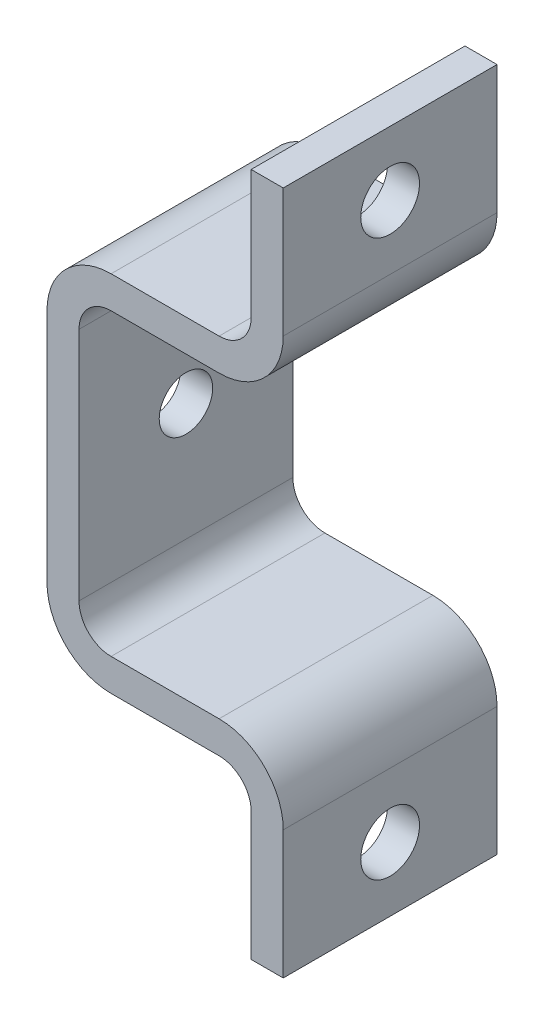
SolidWorks part; units mm, degrees
ref_plane "Front Plane" through (0, 0, 0) normal (0, 0, 1) x (1, 0, 0)
ref_plane "Top Plane" through (0, 0, 0) normal (0, 1, 0) x (1, 0, 0)
ref_plane "Right Plane" through (0, 0, 0) normal (1, 0, 0) x (0, 0, -1)
sketch "Sketch1" plane through (0, 0, 0) normal (0, 0, 1) x (1, 0, 0)
  line L0 (0, -17) -> (0, 17)
  line L1 (0, 17) -> (19.1, 17)
  line L2 (19.1, 17) -> (19.1, 32)
  line L3 (19.1, 32) -> (22.1, 32)
  line L4 (22.1, 32) -> (22.1, 14)
  line L5 (22.1, 14) -> (3, 14)
  line L6 (3, 14) -> (3, -14)
  line L7 (0, 0) -> (30452.2574, 0) construction
  line L8 (22.1, -32) -> (22.1, -14)
  line L9 (19.1, -32) -> (22.1, -32)
  line L10 (19.1, -17) -> (19.1, -32)
  line L11 (0, -17) -> (19.1, -17)
  line L12 (22.1, -14) -> (3, -14)
  point P4 (0, 0)
  point P11 (0, 0)
  point P20 (3, 0)
  dimension "D1" = 3
  dimension "D2" = 3
  dimension "D3" = 3
  dimension "D4" = 15
  dimension "D5" = 28
  dimension "D6" = 19.1
extrude "Boss-Extrude1" add sketch "Sketch1" along normal mid plane 20
fillet "Fillet1" radius 3 4 edges at (19.1, -17, 0) (3, -14, 0) (3, 14, 0) (19.1, 17, 0)
fillet "Fillet2" radius 6 4 edges at (22.1, -14, 0) (0, -17, 0) (0, 17, 0) (22.1, 14, 0)
sketch "Sketch3" plane through (0, 0, 0) normal (-1, 0, 0) x (0, 0, 1)
  line L0 (0, 0) -> (0, 26) construction
  line L1 (-10, 32) -> (-10, 20) construction
  line L2 (-10, 32) -> (-10, 20) construction
  line L3 (-10, 26) -> (0, 26) construction
  line L4 (0, 0) -> (50000, 0) construction
  line L5 (-2.5, 26) -> (2.5, 26) construction
  line L6 (-2.5, 28.5) -> (2.5, 28.5)
  line L7 (-2.5, 23.5) -> (2.5, 23.5)
  line L8 (-2.5, -26) -> (2.5, -26) construction
  line L9 (-2.5, -28.5) -> (2.5, -28.5)
  line L10 (-2.5, -23.5) -> (2.5, -23.5)
  circle A0 centre (0, 0) radius 2.5
  circle A1 centre (0, 26) radius 2.5 construction
  circle A2 centre (0, -26) radius 2.5 construction
  arc A3 (-2.5, 28.5) -> (-2.5, 23.5) centre (-2.5, 26) ccw
  arc A4 (2.5, 23.5) -> (2.5, 28.5) centre (2.5, 26) ccw
  arc A5 (-2.5, -28.5) -> (-2.5, -23.5) centre (-2.5, -26) cw
  arc A6 (2.5, -23.5) -> (2.5, -28.5) centre (2.5, -26) cw
  point P14 (0, 26)
  point P21 (0, -26)
  dimension "D1" = 5
  dimension "D2" = 5
  dimension "D3" = 5
extrude "Cut-Extrude1" cut sketch "Sketch3" against normal through all contours A0 | L7 A4 L6 A3
hole_wizard "Ø5.5 (5.5) Diameter Hole1" positions "Sketch6" profile "Sketch7" hole size "Ø5.5" standard "ISO" end condition through all
sketch "Sketch6" plane through (0, 0, 0) normal (-1, 0, 0) x (0, 0, 1)
  point P0 (0, 26)
  point P3 (0, -26)
sketch "Sketch7" plane through (0, 26, 0) normal (0, 1, 0) x (0, 0, 1)
  line L0 (0, 0) -> (0, 22.1)
  line L1 (0, 22.1) -> (2.75, 22.1)
  line L2 (2.75, 22.1) -> (2.75, 0)
  line L5 (2.75, 0) -> (0, 0)
  line L11 (0, -6.35) -> (0, 107.95) construction
  dimension "Thru Hole Dia." = 5.5
  dimension "Thru Hole Depth" = 22.1
